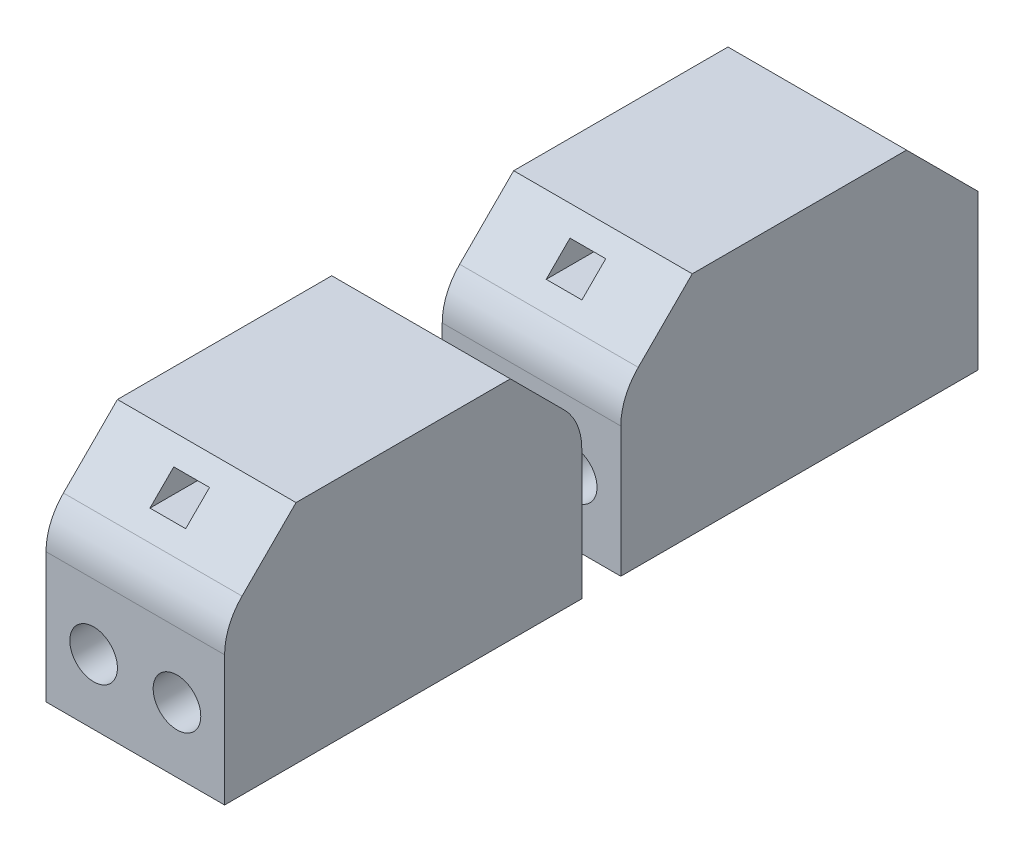
SolidWorks part; units mm, degrees
ref_plane "Front Plane" through (0, 0, 0) normal (0, 0, 1) x (1, 0, 0)
ref_plane "Top Plane" through (0, 0, 0) normal (0, 1, 0) x (1, 0, 0)
ref_plane "Right Plane" through (0, 0, 0) normal (1, 0, 0) x (0, 0, -1)
sketch "Sketch2" plane through (0, 0, 0) normal (1, 0, 0) x (0, 0, -1)
  line L0 (-7.9672, -29.2167) -> (-7.9672, -16.2167)
  line L1 (-7.9672, -16.2167) -> (-1.9672, -10.2167)
  line L2 (-1.9672, -10.2167) -> (16.0328, -10.2167)
  line L3 (16.0328, -10.2167) -> (22.0328, -16.2167)
  line L4 (22.0328, -16.2167) -> (22.0328, -29.2167)
  line L5 (22.0328, -29.2167) -> (-7.9672, -29.2167)
  dimension "D1" = 45
  dimension "D2" = 45
  dimension "D4" = 30
extrude "Boss-Extrude2" add sketch "Sketch2" along normal mid plane 15 separate body
sketch "Sketch3" plane through (0, 0, 0) normal (1, 0, 0) x (0, 0, -1)
  line L0 (25.3112, -16.2167) -> (25.3112, -29.2167)
  line L1 (25.3112, -29.2167) -> (55.3112, -29.2167)
  line L2 (55.3112, -29.2167) -> (55.3112, -16.2167)
  line L3 (55.3112, -16.2167) -> (49.3112, -10.2167)
  line L4 (49.3112, -10.2167) -> (31.3112, -10.2167)
  line L5 (31.3112, -10.2167) -> (25.3112, -16.2167)
  line L6 (16.0328, -10.2167) -> (-1.9672, -10.2167) construction
  line L7 (-7.9672, -29.2167) -> (22.0328, -29.2167) construction
  dimension "D1" = 30
  dimension "D2" = 45
  dimension "D3" = 45
extrude "Boss-Extrude3" add sketch "Sketch3" along normal mid plane 15 separate body
fillet "Fillet1" radius 5 1 edges at (0, -16.2167, -25.3112)
fillet "Fillet2" radius 5 2 edges at (0, -16.2167, 7.9672) (0, -16.2167, -22.0328)
sketch "Sketch4" plane through (0, 0, 0) normal (0, 0, 1) x (1, 0, 0)
  line L3 (-1.5, -11.4845) -> (1.5, -11.4845)
  line L4 (-1.5, -11.4845) -> (-1.5, -13.4845)
  line L5 (-1.5, -13.4845) -> (1.5, -13.4845)
  line L6 (1.5, -11.4845) -> (1.5, -13.4845)
  line L7 (-1.5, -11.4845) -> (1.5, -13.4845) construction
  line L8 (-1.5, -13.4845) -> (1.5, -11.4845) construction
  circle A0 centre (-3.5, -23.7523) radius 2
  circle A1 centre (3.5, -23.7523) radius 2
  point P6 (0, 0)
  point P9 (0, 0)
  point P10 (0, 0)
  point P11 (0, -12.4845)
  dimension "D1" = 4
  dimension "D2" = 4
  dimension "D5" = 3
  dimension "D6" = 2
extrude "Cut-Extrude1" cut sketch "Sketch4" against normal mid plane 200
